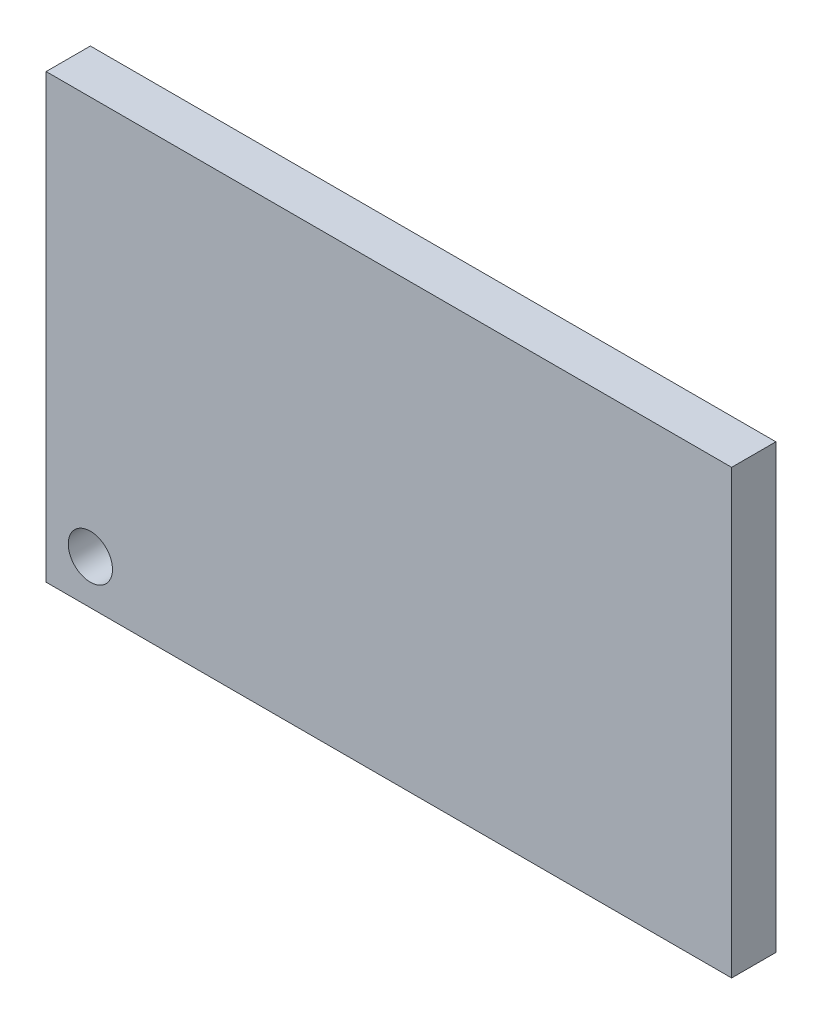
SolidWorks part; units mm, degrees
ref_plane "Front Plane" through (0, 0, 0) normal (0, 0, 1) x (1, 0, 0)
ref_plane "Top Plane" through (0, 0, 0) normal (0, 1, 0) x (1, 0, 0)
ref_plane "Right Plane" through (0, 0, 0) normal (1, 0, 0) x (0, 0, -1)
sketch "Sketch1" plane through (0, 0, 0) normal (0, 0, 1) x (1, 0, 0)
  line L1 (77.5, 50) -> (-77.5, 50)
  line L2 (77.5, 50) -> (77.5, -50)
  line L3 (77.5, -50) -> (-77.5, -50)
  line L4 (-77.5, 50) -> (-77.5, -50)
  line L5 (77.5, 50) -> (-77.5, -50) construction
  line L6 (77.5, -50) -> (-77.5, 50) construction
  point P0 (0, 0)
  dimension "D1" = 155
  dimension "D2" = 100
extrude "Boss-Extrude1" add sketch "Sketch1" along normal blind 10
sketch "Sketch2" plane through (0, 0, 10) normal (0, 0, 1) x (1, 0, 0)
  line L0 (-77.5, -50) -> (77.5, -50) construction
  line L1 (-77.5, 50) -> (-77.5, -50) construction
  circle A0 centre (-67.5, -40) radius 5
  dimension "D3" = 10
  dimension "D1" = 10
  dimension "D2" = 10
extrude "Cut-Extrude1" cut sketch "Sketch2" against normal through all
sketch "Sketch3" plane through (0, 0, 10) normal (0, 0, 1) x (1, 0, 0)
  spline S0 degree 3 poles (-60, 20) (-5.741, 42.3208) (4.2132, -53.2038) (60, 0) knots 0 0 0 0 1 1 1 1
  point P0 (-60, 20)
  point P1 (-16, 12)
  point P2 (10, -10)
  point P3 (60, 0)
  dimension "D1" = 60
  dimension "D2" = 20
  dimension "D3" = 16
  dimension "D4" = 12
  dimension "D5" = 10
  dimension "D6" = 10
  dimension "D7" = 60
